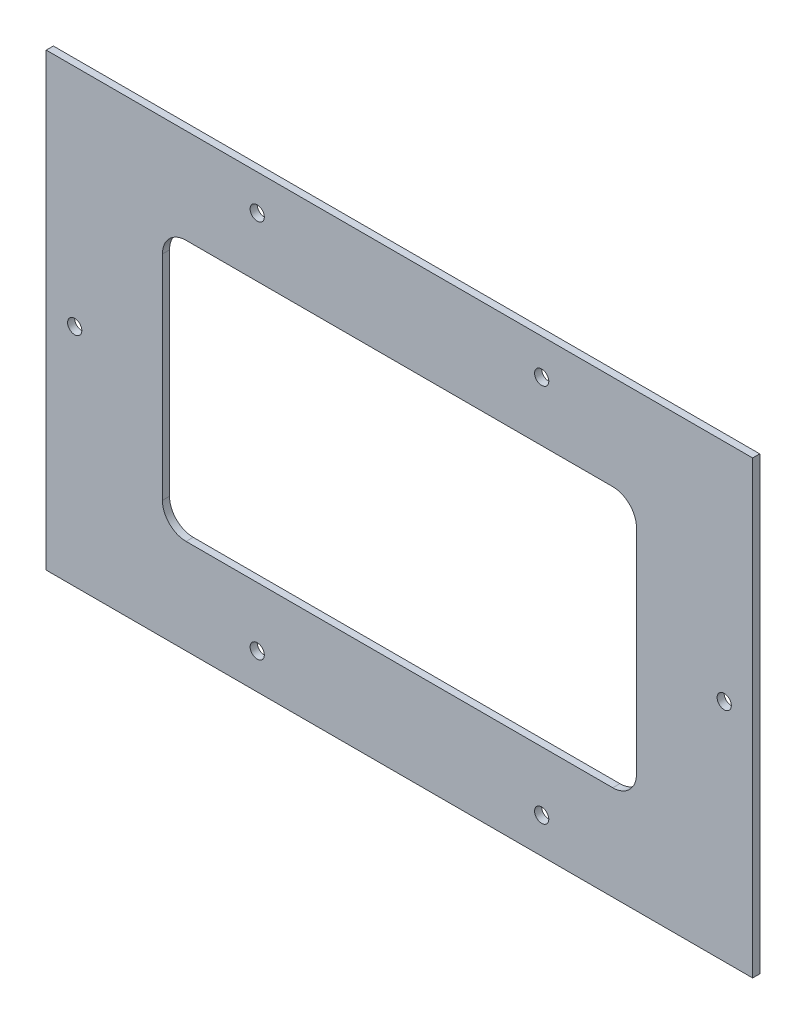
SolidWorks part; units mm, degrees
material "Alliage 1060"
ref_plane "Plan de face" through (0, 0, 0) normal (0, 0, 1) x (1, 0, 0)
ref_plane "Plan de dessus" through (0, 0, 0) normal (0, 1, 0) x (1, 0, 0)
ref_plane "Plan de droite" through (0, 0, 0) normal (1, 0, 0) x (0, 0, -1)
sketch "Esquisse1" plane through (0, 0, 0) normal (0, 0, 1) x (1, 0, 0)
  line L0 (0, 80) -> (0, 0) construction
  line L1 (-74.5, 165) -> (74.5, 165)
  line L2 (-74.5, 165) -> (-74.5, 0)
  line L3 (-74.5, 0) -> (74.5, 0)
  line L4 (74.5, 165) -> (74.5, 0)
  line L5 (-50, 135) -> (50, 135)
  line L6 (-50, 135) -> (-50, 80)
  line L7 (-50, 80) -> (50, 80)
  line L8 (50, 135) -> (50, 80)
  dimension "D1" = 165
  dimension "D2" = 149
  dimension "D3" = 55
  dimension "D4" = 100
  dimension "D5" = 80
extrude "Boss.-Extru.1" add sketch "Esquisse1" along normal blind 1.5
fillet "Congé1" radius 5 4 edges at (50, 80, 0.75) (50, 135, 0.75) (-50, 135, 0.75) (-50, 80, 0.75)
sketch "Esquisse2" plane through (0, 0, 1.5) normal (0, 0, 1) x (1, 0, 0)
  line L0 (-50, 107.5) -> (0, 107.5) construction
  line L1 (-50, 130) -> (-50, 85) construction
  line L2 (0, 107.5) -> (0, 135) construction
  line L3 (45, 135) -> (-45, 135) construction
  line L4 (-74.5, 82.5) -> (74.5, 82.5) construction
  line L5 (-74.5, 165) -> (-74.5, 0) construction
  line L6 (74.5, 0) -> (74.5, 165) construction
  line L7 (74.5, 165) -> (-74.5, 165) construction
  circle A0 centre (-30, 147.5) radius 1.5
  circle A1 centre (-30, 67.5) radius 1.5
  circle A2 centre (30, 67.5) radius 1.5
  circle A3 centre (30, 147.5) radius 1.5
  circle A4 centre (-55, 160) radius 1.5
  circle A5 centre (-55, 5) radius 1.5
  circle A6 centre (55, 5) radius 1.5
  circle A7 centre (55, 160) radius 1.5
  dimension "D1" = 80
  dimension "D2" = 3
  dimension "D3" = 60
  dimension "D4" = 5
  dimension "D5" = 110
  dimension "D6" = 155
extrude "Enlèv. mat.-Extru.1" cut sketch "Esquisse2" against normal through all
sketch "Esquisse3" plane through (0, 0, 1.5) normal (0, 0, 1) x (1, 0, 0)
  line L0 (74.5, 0) -> (74.5, 165) construction
  line L1 (-74.5, 165) -> (74.5, 165)
  line L2 (-74.5, 165) -> (-74.5, 155)
  line L3 (-74.5, 155) -> (74.5, 155)
  line L4 (74.5, 165) -> (74.5, 155)
  line L5 (-74.5, 165) -> (-74.5, 0) construction
  line L6 (74.5, 0) -> (-74.5, 0)
  line L7 (74.5, 0) -> (74.5, 60)
  line L8 (74.5, 60) -> (-74.5, 60)
  line L9 (-74.5, 0) -> (-74.5, 60)
  line L10 (-50, 107.5) -> (50, 107.5) construction
  line L11 (-50, 130) -> (-50, 85) construction
  line L12 (50, 85) -> (50, 130) construction
  line L13 (0, -0.825) -> (0, 0.825) construction
  circle A0 centre (-30, 147.5) radius 1.5 construction
  circle A1 centre (-68.5, 107.5) radius 1.5
  circle A2 centre (68.5, 107.5) radius 1.5
  dimension "D1" = 7.5
  dimension "D3" = 6
  dimension "D4" = 3
  dimension "D2" = 95
extrude "Enlèv. mat.-Extru.2" cut sketch "Esquisse3" against normal through all
